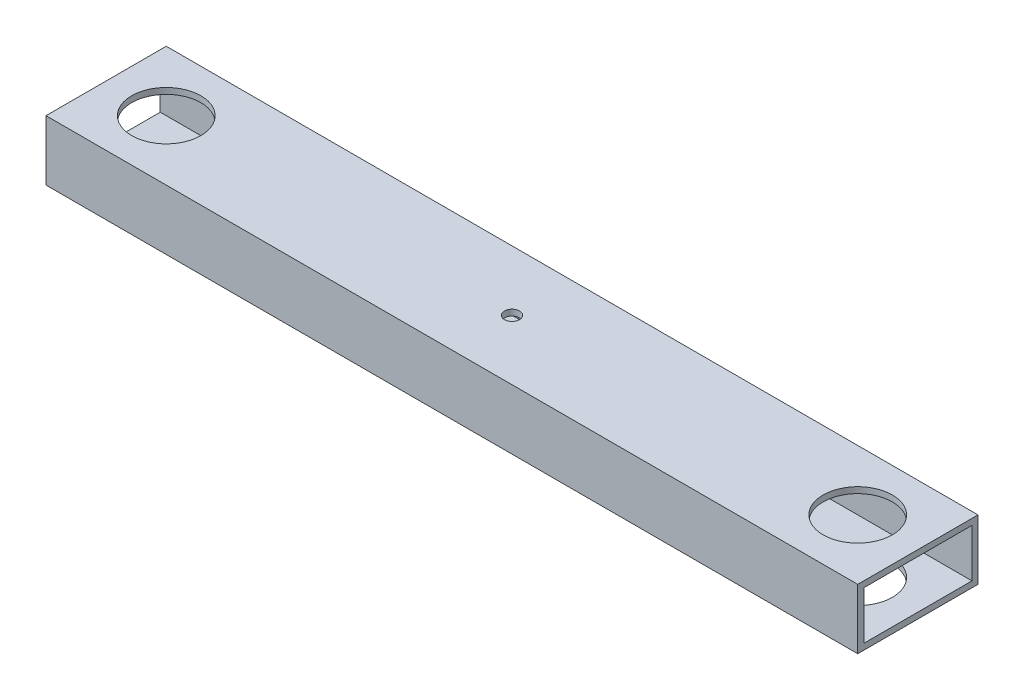
SolidWorks part; units mm, degrees
ref_plane "Front Plane" through (0, 0, 0) normal (0, 0, 1) x (1, 0, 0)
ref_plane "Top Plane" through (0, 0, 0) normal (0, 1, 0) x (1, 0, 0)
ref_plane "Right Plane" through (0, 0, 0) normal (1, 0, 0) x (0, 0, -1)
sketch "Sketch1" plane through (0, 0, 0) normal (1, 0, 0) x (0, 0, -1)
  line L0 (-22.86, 10.16) -> (22.86, 10.16)
  line L1 (-25.4, -12.7) -> (25.4, -12.7)
  line L2 (-25.4, -12.7) -> (-25.4, 12.7)
  line L3 (-25.4, 12.7) -> (25.4, 12.7)
  line L4 (25.4, -12.7) -> (25.4, 12.7)
  line L5 (-25.4, -12.7) -> (25.4, 12.7) construction
  line L6 (-25.4, 12.7) -> (25.4, -12.7) construction
  line L7 (22.86, -10.16) -> (22.86, 10.16)
  line L8 (-22.86, -10.16) -> (22.86, -10.16)
  line L9 (-22.86, -10.16) -> (-22.86, 10.16)
  point P0 (0, 0)
  dimension "D1" = 25.4
  dimension "D2" = 50.8
  dimension "D3" = 2.54
extrude "Boss-Extrude1" add sketch "Sketch1" along normal blind 342.9
sketch "Sketch2" plane through (0, -12.7, 0) normal (0, -1, 0) x (1, 0, 0)
  line L0 (171.45, -25.4) -> (171.45, 25.4) construction
  line L1 (342.9, -25.4) -> (0, -25.4) construction
  line L2 (342.9, 25.4) -> (0, 25.4) construction
  line L3 (0, 0) -> (342.9, 0) construction
  line L4 (0, 25.4) -> (0, -25.4) construction
  circle A0 centre (25.4, 0) radius 14.605
  circle A1 centre (317.5, 0) radius 14.605
  point P14 (171.45, 0)
  dimension "D1" = 29.21
  dimension "D3" = 25.4
  dimension "D2" = 25.4
extrude "Cut-Extrude1" cut sketch "Sketch2" against normal through all
sketch "Sketch6" plane through (0, -12.7, 0) normal (0, -1, 0) x (1, 0, 0)
  circle A0 centre (171.45, 0) radius 3.175
  dimension "D1" = 6.35
extrude "Cut-Extrude5" cut sketch "Sketch6" against normal through all
